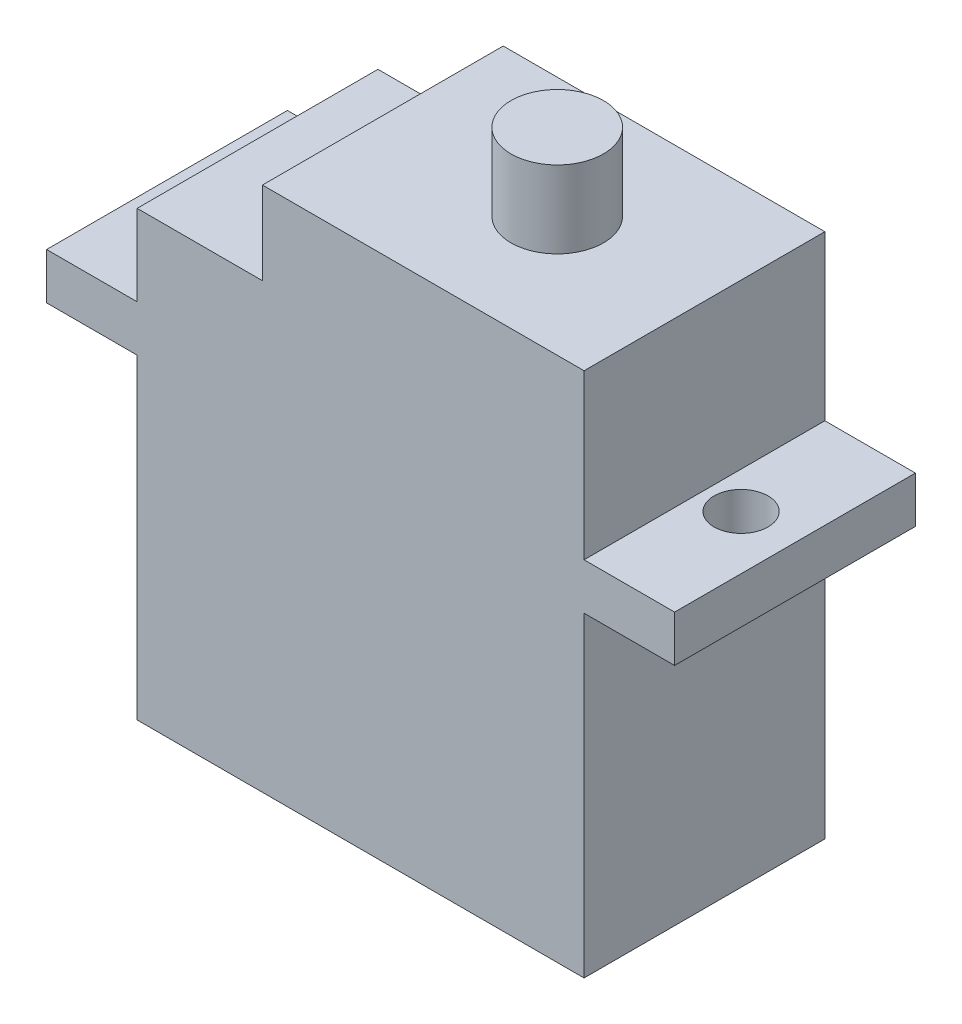
SolidWorks part; units mm, degrees
ref_plane "Front Plane" through (0, 0, 0) normal (0, 0, 1) x (1, 0, 0)
ref_plane "Top Plane" through (0, 0, 0) normal (0, 1, 0) x (1, 0, 0)
ref_plane "Right Plane" through (0, 0, 0) normal (1, 0, 0) x (0, 0, -1)
sketch "Sketch1" plane through (0, 0, 0) normal (0, 0, 1) x (1, 0, 0)
  line L0 (0, 18.8) -> (0, 23)
  line L1 (0, 0) -> (23.2, 0)
  line L2 (0, 0) -> (0, 16.4)
  line L3 (0, 23) -> (6.504, 23)
  line L4 (23.2, 0) -> (23.2, 16.4)
  line L5 (0, 18.8) -> (-4.7, 18.8)
  line L7 (0, 16.4) -> (-4.7, 16.4)
  line L8 (-4.7, 18.8) -> (-4.7, 16.4)
  line L9 (23.2, 18.8) -> (27.9, 18.8)
  line L11 (23.2, 16.4) -> (27.9, 16.4)
  line L12 (27.9, 18.8) -> (27.9, 16.4)
  line L14 (23.2, 23) -> (23.2, 27.3)
  line L15 (23.2, 27.3) -> (6.504, 27.3)
  line L16 (6.504, 23) -> (6.504, 27.3)
  line L17 (23.2, 18.8) -> (23.2, 23)
  point P16 (27.9, 17.6)
  dimension "D1" = 23.2
  dimension "D2" = 23
  dimension "D3" = 2.4
  dimension "D4" = 2.4
  dimension "D5" = 16.4
  dimension "D6" = 16.4
  dimension "D7" = 4.3
  dimension "D8" = 4.7
  dimension "D9" = 4.7
extrude "Boss-Extrude1" add sketch "Sketch1" along normal blind 12.5
sketch "Sketch2" plane through (0, 27.3, 0) normal (0, 1, 0) x (1, 0, 0)
  line L0 (27.9, -12.5) -> (27.9, 0) construction
  line L1 (-4.7, -12.5) -> (-4.7, 0) construction
  circle A0 centre (-1.9, -6.25) radius 1.4
  circle A1 centre (25.1, -6.25) radius 1.4
  point P4 (-3.6303, -6.25)
  point P5 (0, 0)
  point P10 (0, 0)
  dimension "D1" = 2.8
  dimension "D2" = 2.8
  dimension "D3" = 27
  dimension "D4" = 2.8
  dimension "D5" = 2.8
extrude "Cut-Extrude1" cut sketch "Sketch2" against normal blind 12.5
sketch "Sketch3" plane through (0, 27.3, 0) normal (0, 1, 0) x (1, 0, 0)
  circle A0 centre (15.5569, -6.25) radius 2.4
  dimension "D1" = 4.8
extrude "Boss-Extrude2" add sketch "Sketch3" along normal blind 4 contours A0
